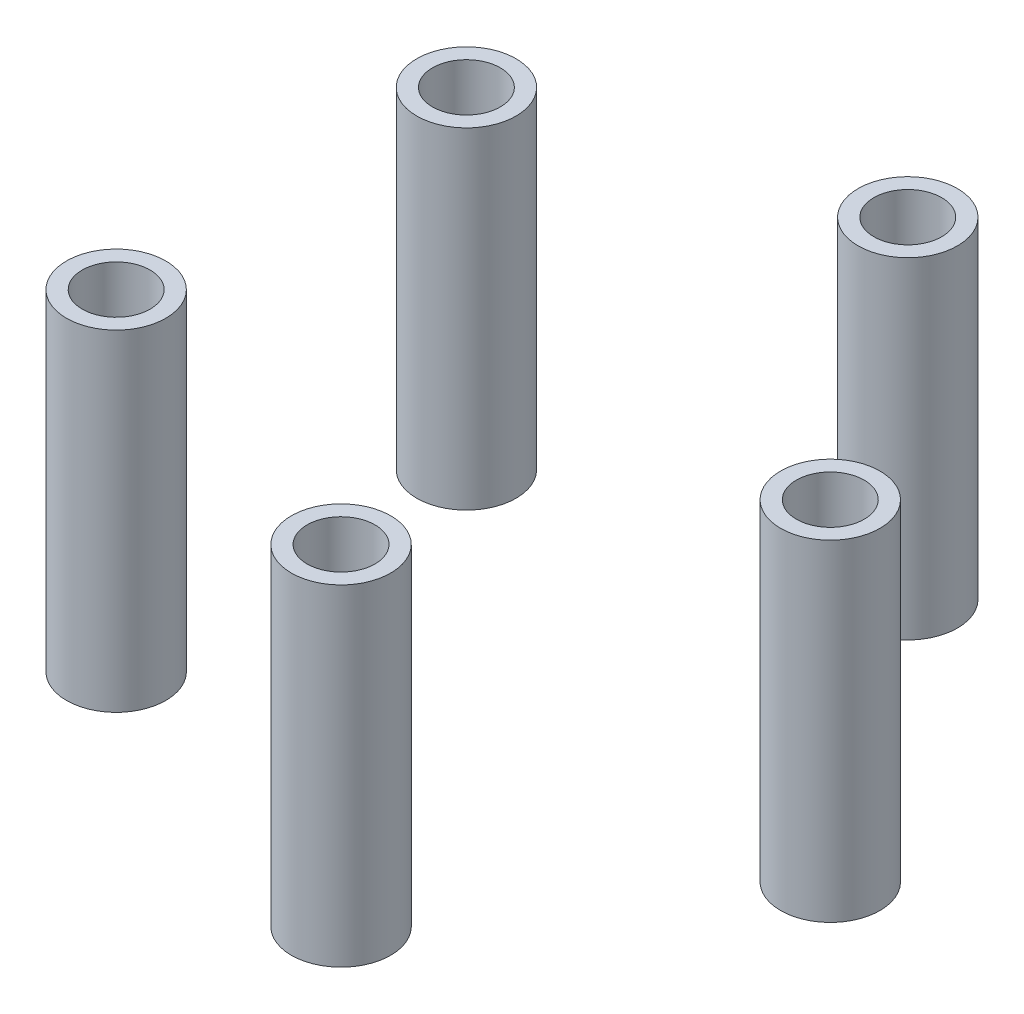
SolidWorks part; units mm, degrees
ref_plane "Front Plane" through (0, 0, 0) normal (0, 0, 1) x (1, 0, 0)
ref_plane "Top Plane" through (0, 0, 0) normal (0, 1, 0) x (1, 0, 0)
ref_plane "Right Plane" through (0, 0, 0) normal (1, 0, 0) x (0, 0, -1)
sketch "Sketch1" plane through (0, 0, 0) normal (0, 1, 0) x (1, 0, 0)
  line L0 (-18.8623, 10.5801) -> (-12.6623, 10.5801) construction
  line L1 (1.2623, 17.119) -> (7.4623, 17.119) construction
  line L2 (13.7, 0) -> (19.9, 0) construction
  line L3 (1.2623, -17.119) -> (7.4623, -17.119) construction
  line L4 (-18.8623, -10.5801) -> (-12.6623, -10.5801) construction
  circle A0 centre (-14.5623, 10.5801) radius 4.3 construction
  circle A1 centre (-16.9623, 10.5801) radius 4.3 construction
  circle A4 centre (5.5623, 17.119) radius 4.3 construction
  circle A5 centre (3.1623, 17.119) radius 4.3 construction
  circle A6 centre (18, 0) radius 4.3 construction
  circle A7 centre (15.6, 0) radius 4.3 construction
  circle A8 centre (5.5623, -17.119) radius 4.3 construction
  circle A9 centre (3.1623, -17.119) radius 4.3 construction
  circle A10 centre (-14.5623, -10.5801) radius 4.3 construction
  circle A11 centre (-16.9623, -10.5801) radius 4.3 construction
  circle A12 centre (-15.7623, -10.5801) radius 3
  circle A13 centre (4.3623, -17.119) radius 3
  circle A14 centre (16.8, 0) radius 3
  circle A15 centre (16.8, 0) radius 2.05
  circle A16 centre (4.3623, -17.119) radius 2.05
  circle A17 centre (-15.7623, -10.5801) radius 2.05
  circle A18 centre (-15.7623, 10.5801) radius 2.05
  circle A19 centre (-15.7623, 10.5801) radius 3
  circle A20 centre (4.3623, 17.119) radius 3
  circle A21 centre (4.3623, 17.119) radius 2.05
  dimension "D1" = 6
extrude "Boss-Extrude1" add sketch "Sketch1" along normal blind 12 and the other way blind 8
